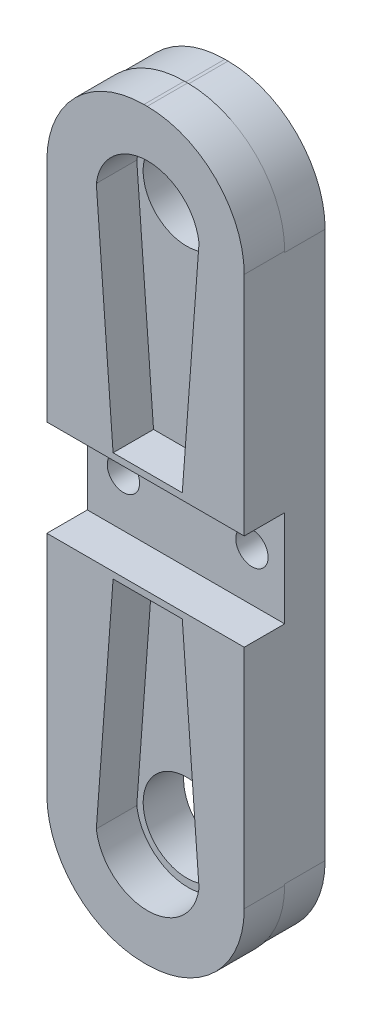
SolidWorks part; units mm, degrees
ref_plane "Front Plane" through (0, 0, 0) normal (0, 0, 1) x (1, 0, 0)
ref_plane "Top Plane" through (0, 0, 0) normal (0, 1, 0) x (1, 0, 0)
ref_plane "Right Plane" through (0, 0, 0) normal (1, 0, 0) x (0, 0, -1)
other "Graphic1"
other "object_1 (Open) -1"
ref_plane "Plane1" through (0, 0, 10) normal (0, 0, 1) x (1, 0, 0)
sketch "Sketch1" plane through (0, 0, 10) normal (0, 0, 1) x (1, 0, 0)
  line L1 (-188.2312, 182.8882) -> (-176.0312, 182.8882)
  line L2 (-188.2312, 182.8882) -> (-188.2312, 137.0882)
  line L3 (-188.2312, 137.0882) -> (-176.0312, 137.0882)
  line L4 (-176.0312, 182.8882) -> (-176.0312, 137.0882)
  dimension "D1" = 12.2
  dimension "D2" = 45.8
extrude "Boss-Extrude1" add sketch "Sketch1" along normal blind 2.5
fillet "Fillet1" radius 6 4 edges at (-176.0312, 182.8882, 11.25) (-188.2312, 182.8882, 11.25) (-176.0312, 137.0882, 11.25) (-188.2312, 137.0882, 11.25)
sketch "Sketch2" plane through (0, 0, 12.5) normal (0, 0, 1) x (1, 0, 0)
  line L0 (-188.2312, 159.9882) -> (-146.0551, 159.9882) construction
  line L2 (-176.0312, 143.0882) -> (-176.0312, 176.8882) construction
  line L3 (-176.0312, 162.9655) -> (-188.2312, 162.9655)
  line L4 (-176.0312, 162.9655) -> (-176.0312, 182.9655)
  line L5 (-176.0312, 182.9655) -> (-188.2312, 182.9655)
  line L6 (-188.2312, 162.9655) -> (-188.2312, 182.9655)
  line L7 (-188.2312, 176.8882) -> (-188.2312, 143.0882) construction
  line L8 (-176.0312, 137.0109) -> (-188.2312, 137.0109)
  line L9 (-188.2312, 157.0109) -> (-188.2312, 137.0109)
  line L10 (-176.0312, 157.0109) -> (-188.2312, 157.0109)
  line L11 (-176.0312, 157.0109) -> (-176.0312, 137.0109)
  dimension "D1" = 20
  dimension "D2" = 12.2
extrude "Boss-Extrude2" add sketch "Sketch2" along normal blind 2.5
fillet "Fillet2" radius 6 4 edges at (-188.2312, 182.9655, 13.75) (-176.0312, 182.9655, 13.75) (-188.2312, 137.0109, 13.75) (-176.0312, 137.0109, 13.75)
sketch "Sketch3" plane through (0, 0, 12.5) normal (0, 0, 1) x (1, 0, 0)
  circle A0 centre (-185.9997, 160.0579) radius 1
  circle A1 centre (-178.0549, 160.0579) radius 1
extrude "Cut-Extrude1" cut sketch "Sketch3" against normal blind 2.5
sketch "Sketch4" plane through (0, 0, 15) normal (0, 0, 1) x (1, 0, 0)
  line L0 (-184.1384, 163.3657) -> (-179.8616, 163.3657)
  line L1 (-179.8616, 163.3657) -> (-178.8249, 177.2648)
  line L2 (-184.1384, 163.3657) -> (-185.1751, 177.2648)
  line L3 (-176.0312, 159.9882) -> (-170.1506, 159.9882) construction
  line L4 (-176.0312, 157.0109) -> (-176.0312, 162.9655) construction
  line L5 (-184.1384, 156.6106) -> (-185.1751, 142.7116)
  line L6 (-184.1384, 156.6106) -> (-179.8616, 156.6106)
  line L7 (-179.8616, 156.6106) -> (-178.8249, 142.7116)
  arc A0 (-185.1751, 177.2648) -> (-178.8249, 177.2648) centre (-182, 176.8585) cw
  arc A1 (-185.1751, 142.7116) -> (-178.8249, 142.7116) centre (-182, 143.1178) ccw
extrude "Cut-Extrude2" cut sketch "Sketch4" against normal up to vertex (2.5 mm away)
sketch "Sketch5" plane through (0, 0, 12.5) normal (0, 0, 1) x (1, 0, 0)
  line L0 (-176.0312, 159.9882) -> (-170.9247, 159.9882) construction
  line L1 (-176.0312, 157.0109) -> (-176.0312, 162.9655) construction
  circle A0 centre (-182.0806, 176.9002) radius 2.7
  circle A1 centre (-182.0806, 143.0762) radius 2.7
extrude "Cut-Extrude3" cut sketch "Sketch5" against normal blind 2.5
